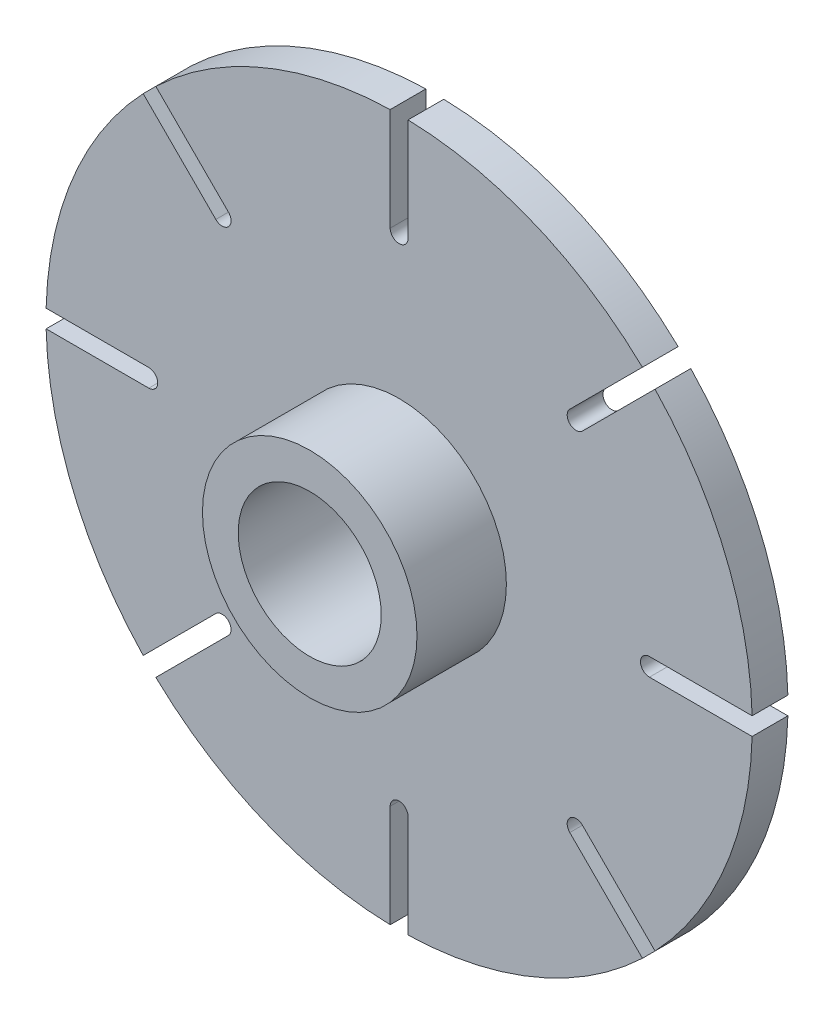
SolidWorks part; units mm, degrees
ref_plane "Front Plane" through (0, 0, 0) normal (0, 0, 1) x (1, 0, 0)
ref_plane "Top Plane" through (0, 0, 0) normal (0, 1, 0) x (1, 0, 0)
ref_plane "Right Plane" through (0, 0, 0) normal (1, 0, 0) x (0, 0, -1)
sketch "Sketch1" plane through (0, 0, 0) normal (0, 0, 1) x (1, 0, 0)
  circle A0 centre (0, 0) radius 4
  circle A1 centre (0, 0) radius 6
  dimension "D1" = 8
  dimension "D2" = 2
extrude "Boss-Extrude1" add sketch "Sketch1" along normal blind 7
sketch "Sketch2" plane through (0, 0, 0) normal (0, 0, -1) x (-1, 0, 0)
  line L0 (0, 0) -> (0, 19.75) construction
  line L1 (-0.5, 14) -> (-0.5, 19.7437)
  line L2 (0.5, 14) -> (0.5, 19.7437)
  line L3 (9.5459, 10.253) -> (13.6073, 14.3144)
  line L4 (10.253, 9.5459) -> (14.3144, 13.6073)
  line L5 (14, 0.5) -> (19.7437, 0.5)
  line L6 (14, -0.5) -> (19.7437, -0.5)
  line L7 (10.253, -9.5459) -> (14.3144, -13.6073)
  line L8 (9.5459, -10.253) -> (13.6073, -14.3144)
  line L9 (0.5, -14) -> (0.5, -19.7437)
  line L10 (-0.5, -14) -> (-0.5, -19.7437)
  line L11 (-9.5459, -10.253) -> (-13.6073, -14.3144)
  line L12 (-10.253, -9.5459) -> (-14.3144, -13.6073)
  line L13 (-14, -0.5) -> (-19.7437, -0.5)
  line L14 (-14, 0.5) -> (-19.7437, 0.5)
  line L15 (-10.253, 9.5459) -> (-14.3144, 13.6073)
  line L16 (-9.5459, 10.253) -> (-13.6073, 14.3144)
  circle A0 centre (0, 0) radius 19.75
  circle A1 centre (0, 14) radius 0.5
  circle A11 centre (0, 0) radius 6 construction
  circle A12 centre (9.8995, 9.8995) radius 0.5
  circle A13 centre (14, 0) radius 0.5
  circle A14 centre (9.8995, -9.8995) radius 0.5
  circle A15 centre (0, -14) radius 0.5
  circle A16 centre (-9.8995, -9.8995) radius 0.5
  circle A17 centre (-14, 0) radius 0.5
  circle A18 centre (-9.8995, 9.8995) radius 0.5
  point P10 (0, 6)
  dimension "D1" = 39.5
  dimension "D2" = 1
  dimension "D3" = 8
  dimension "D4" = 8
extrude "Boss-Extrude2" add sketch "Sketch2" against normal blind 2
